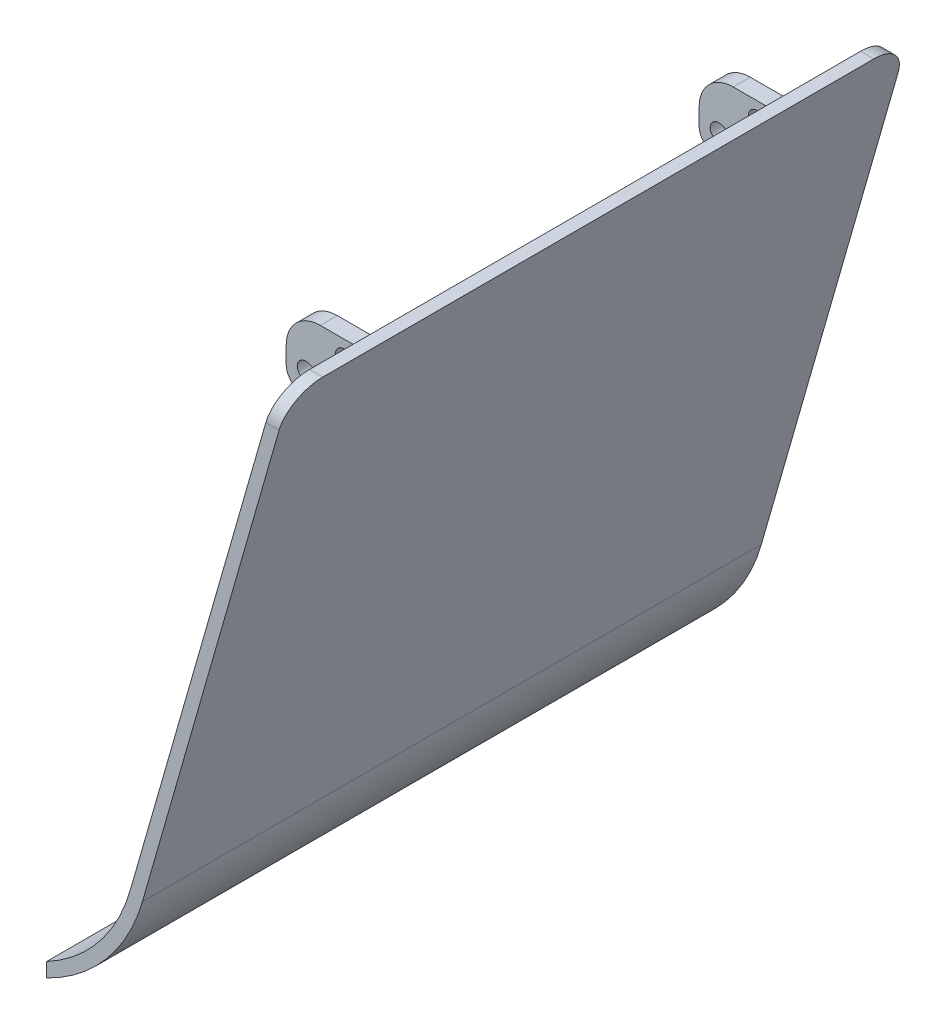
SolidWorks part; units mm, degrees
ref_plane "Front Plane" through (0, 0, 0) normal (0, 0, 1) x (1, 0, 0)
ref_plane "Top Plane" through (0, 0, 0) normal (0, 1, 0) x (1, 0, 0)
ref_plane "Right Plane" through (0, 0, 0) normal (1, 0, 0) x (0, 0, -1)
sketch "Sketch1" plane through (0, 0, 0) normal (0, 0, 1) x (1, 0, 0)
  line L0 (0, 0) -> (-18.2728, 0) construction
  line L1 (0, 0) -> (-17.1109, -59.6727)
  line L2 (0.3169, 1.105) -> (0, 0) construction
  line L3 (1.4419, -0.4135) -> (-15.669, -60.0862)
  line L4 (0, 0) -> (1.5604, 0)
  line L5 (-31.2406, -73.5) -> (-30.8584, -74.9505)
  line L6 (1.7588, 0.6916) -> (1.4419, -0.4135) construction
  line L7 (1.5604, 0) -> (1.4419, -0.4135)
  arc A0 (-30.8584, -74.9505) -> (-15.669, -60.0862) centre (-36.3361, -54.16) ccw
  arc A2 (-31.2406, -73.5) -> (-17.1109, -59.6727) centre (-36.3361, -54.16) ccw
  dimension "D6" = 59.6727
  dimension "D5" = 20
  dimension "D2" = 73.5
  dimension "D1" = 74
  dimension "D4" = 1.5
extrude "Boss-Extrude1" add sketch "Sketch1" along normal mid plane 72.85
sketch "Sketch2" plane through (0, 0, 36.425) normal (0, 0, 1) x (1, 0, 0)
  line L0 (-31.2406, -73.5) -> (-26.9439, -73.5)
  line L1 (-31.2406, -73.5) -> (-30.8584, -74.9505) construction
  line L2 (-31.2406, -73.5) -> (-30.8584, -74.9505)
  arc A0 (-31.2406, -73.5) -> (-17.1109, -59.6727) centre (-36.3361, -54.16) ccw construction
  arc A1 (-30.8584, -74.9505) -> (-15.669, -60.0862) centre (-36.3361, -54.16) ccw construction
  arc A2 (-30.8584, -74.9505) -> (-26.9439, -73.5) centre (-36.3361, -54.16) ccw
extrude "Cut-Extrude1" cut sketch "Sketch2" against normal through all
sketch "Sketch3" plane through (0, 0, 36.425) normal (0, 0, 1) x (1, 0, 0)
  line L0 (-26.9439, -73.5) -> (-31.2406, -73.5) construction
  line L1 (-26.9439, -73.5) -> (-31.2406, -73.5)
  line L2 (-26.9439, -73.5) -> (-26.9439, -71.8175)
  arc A0 (-31.2406, -73.5) -> (-17.1109, -59.6727) centre (-36.3361, -54.16) ccw construction
  arc A1 (-31.2406, -73.5) -> (-26.9439, -71.8175) centre (-36.3361, -54.16) ccw
extrude "Cut-Extrude2" cut sketch "Sketch3" against normal through all
fillet "Fillet1" radius 4 2 edges at (0.7802, 0, -36.425) (0.7802, 0, 36.425)
sketch "Sketch11" plane through (0, 0, 0) normal (0, 0, 1) x (1, 0, 0)
  line L1 (-2.8942, -10.0932) -> (-4.8167, -9.542)
  line L2 (-1.147, -4) -> (-17.1109, -59.6727) construction
  line L3 (-4.8167, -9.542) -> (-3.3283, -4.3512)
  line L5 (-3.3283, -4.3512) -> (-6.2121, -3.5242)
  line L6 (-6.2121, -3.5242) -> (-8.5274, -11.5988)
  line L7 (-8.5274, -11.5988) -> (-3.7211, -12.977)
  line L8 (-3.7211, -12.977) -> (-2.8942, -10.0932)
  dimension "D1" = 3
  dimension "D2" = 10.5
  dimension "D3" = 5
  dimension "D4" = 3
  dimension "D5" = 8.4
sketch "Sketch33" plane through (0, 0, 0) normal (0, 0, 1) x (1, 0, 0)
  line L0 (-0.5735, -2) -> (-9.8675, -2)
  line L1 (0, 0) -> (-1.147, -4) construction
  line L2 (-9.8675, -2) -> (-9.8675, -10)
  line L3 (-9.8675, -10) -> (-2.8675, -10)
  line L4 (-1.147, -4) -> (-17.1109, -59.6727) construction
  line L5 (-2.8675, -10) -> (-0.5735, -2)
  line L6 (0, 0) -> (1.5604, 0) construction
  dimension "D1" = 7
  dimension "D2" = 2
  dimension "D3" = 8
extrude "Boss-Extrude14" add sketch "Sketch33" against normal blind 2 from offset 25.3
sketch "Sketch34" plane through (0, 0, 25.3) normal (0, 0, 1) x (1, 0, 0)
  line L0 (-3.073, -4) -> (-3.073, 1.3792) construction
  line L2 (-3.073, -4) -> (-3.073, 0) construction
  arc A0 (-2.0909, -3.8119) -> (-4.0551, -4.1881) centre (-3.073, -4) ccw
  arc A1 (-7.1489, -6.5944) -> (-7.9971, -8.4056) centre (-7.573, -7.5) ccw
  arc A2 (-7.1489, -6.5944) -> (-4.0551, -4.1881) centre (-6.2159, -4.602) ccw
  arc A3 (-7.9971, -8.4056) -> (-2.0909, -3.8119) centre (-6.2159, -4.602) ccw
  arc A4 (-7.1489, -6.5944) -> (-4.0551, -4.1881) centre (-6.2159, -4.602) ccw construction
  dimension "D1" = 2
  dimension "D4" = 3.5
  dimension "D2" = 4.2
  dimension "D3" = 4.5
extrude "Cut-Extrude10" cut sketch "Sketch34" against normal blind 5
fillet "Fillet13" radius 4 1 edges at (-9.8675, -2, 24.3)
fillet "Fillet14" radius 2 1 edges at (-9.8675, -10, 24.3)
mirror "Mirror1" about plane through (0, 0, 0) normal (0, 0, 1) of "Fillet14", "Fillet13", "Cut-Extrude10", "Boss-Extrude14"
